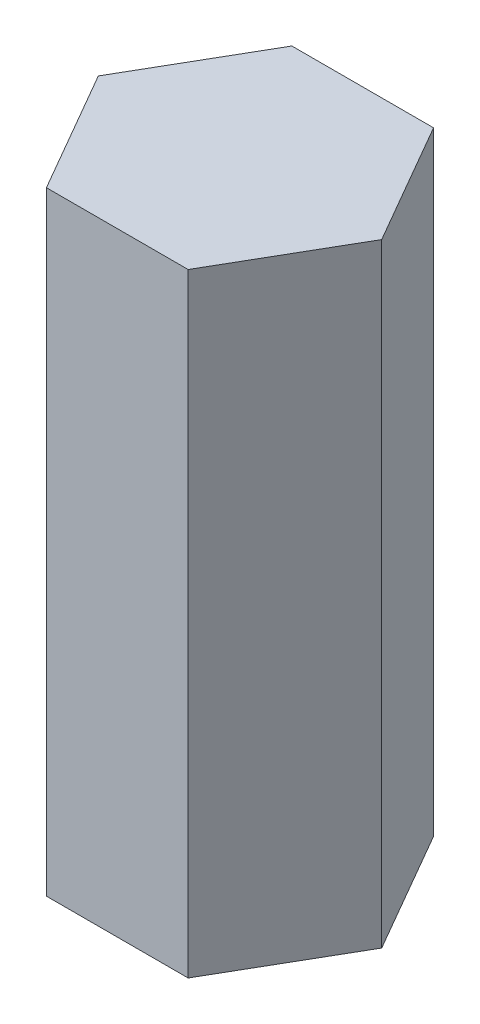
SolidWorks part; units mm, degrees
ref_plane "Front Plane" through (0, 0, 0) normal (0, 0, 1) x (1, 0, 0)
ref_plane "Top Plane" through (0, 0, 0) normal (0, 1, 0) x (1, 0, 0)
ref_plane "Right Plane" through (0, 0, 0) normal (1, 0, 0) x (0, 0, -1)
sketch "Sketch1" plane through (0, 0, 0) normal (0, 1, 0) x (1, 0, 0)
  line L1 (1.6166, 2.8) -> (-1.6166, 2.8)
  line L2 (-1.6166, 2.8) -> (-3.2332, 0)
  line L3 (-3.2332, 0) -> (-1.6166, -2.8)
  line L4 (-1.6166, -2.8) -> (1.6166, -2.8)
  line L5 (1.6166, -2.8) -> (3.2332, 0)
  line L6 (3.2332, 0) -> (1.6166, 2.8)
  circle A0 centre (0, 0) radius 2.8 construction
  point P1 (0, 0)
  dimension "D1" = 5.6
extrude "Boss-Extrude1" add sketch "Sketch1" along normal blind 14
sketch "Sketch2" plane through (0, 14, 0) normal (0, 1, 0) x (1, 0, 0)
  circle A0 centre (0, 0) radius 3.2332 construction
sketch "Sketch3" plane through (0, 0, 0) normal (0, -1, 0) x (1, 0, 0)
  circle A0 centre (0, 0) radius 3.2332
